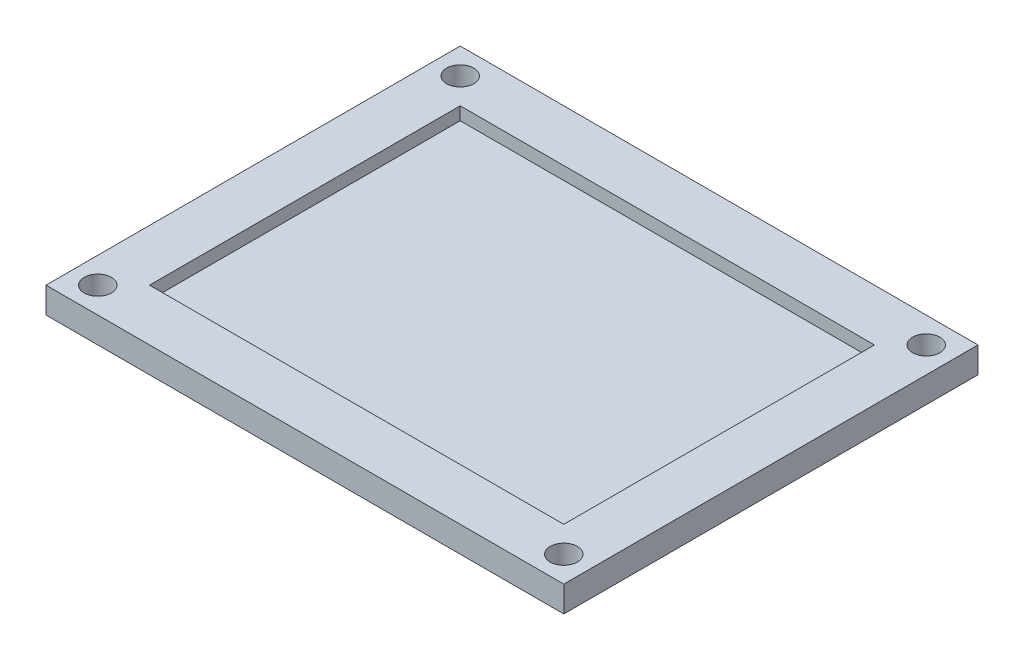
SolidWorks part; units mm, degrees
ref_plane "Front Plane" through (0, 0, 0) normal (0, 0, 1) x (1, 0, 0)
ref_plane "Top Plane" through (0, 0, 0) normal (0, 1, 0) x (1, 0, 0)
ref_plane "Right Plane" through (0, 0, 0) normal (1, 0, 0) x (0, 0, -1)
sketch "Sketch1" plane through (0, 0, 0) normal (0, 1, 0) x (1, 0, 0)
  line L1 (100, -80) -> (-100, -80)
  line L2 (100, -80) -> (100, 80)
  line L3 (100, 80) -> (-100, 80)
  line L4 (-100, -80) -> (-100, 80)
  line L5 (100, -80) -> (-100, 80) construction
  line L6 (100, 80) -> (-100, -80) construction
  point P0 (0, 0)
  dimension "D1" = 200
  dimension "D2" = 160
extrude "Boss-Extrude3" add sketch "Sketch1" along normal blind 10
sketch "Sketch3" plane through (0, 10, 0) normal (0, 1, 0) x (1, 0, 0)
  line L0 (-100, 80) -> (-80, 60) construction
  line L1 (-80, 60) -> (80, 60)
  line L2 (-80, 60) -> (-80, -60)
  line L3 (-80, -60) -> (80, -60)
  line L4 (80, 60) -> (80, -60)
  line L5 (-80, 60) -> (80, -60) construction
  line L6 (-80, -60) -> (80, 60) construction
  line L7 (80, 60) -> (100, 80) construction
  line L8 (-80, -60) -> (-100, -80) construction
  line L12 (80, -60) -> (100, -80) construction
  circle A0 centre (-90, 70) radius 5.25
  circle A2 centre (90, -70) radius 5.25
  circle A4 centre (90, 70) radius 5.25
  circle A5 centre (-90, -70) radius 5.25
  point P0 (0, 0)
  dimension "D3" = 10.5
  dimension "D4" = 10.5
  dimension "D5" = 10.5
  dimension "D6" = 10.5
  dimension "D1" = 160
  dimension "D2" = 120
extrude "Cut-Extrude2" cut sketch "Sketch3" along direction (0, 1, 0) on the side against the normal blind 5
sketch "Sketch6" plane through (0, 5, 0) normal (0, 1, 0) x (1, 0, 0)
  circle A0 centre (-90, 70) radius 5.25
  circle A1 centre (90, 70) radius 5.25
  circle A2 centre (90, -70) radius 5.25
  circle A3 centre (-90, -70) radius 5.25
extrude "Cut-Extrude4" cut sketch "Sketch6" against normal through all
